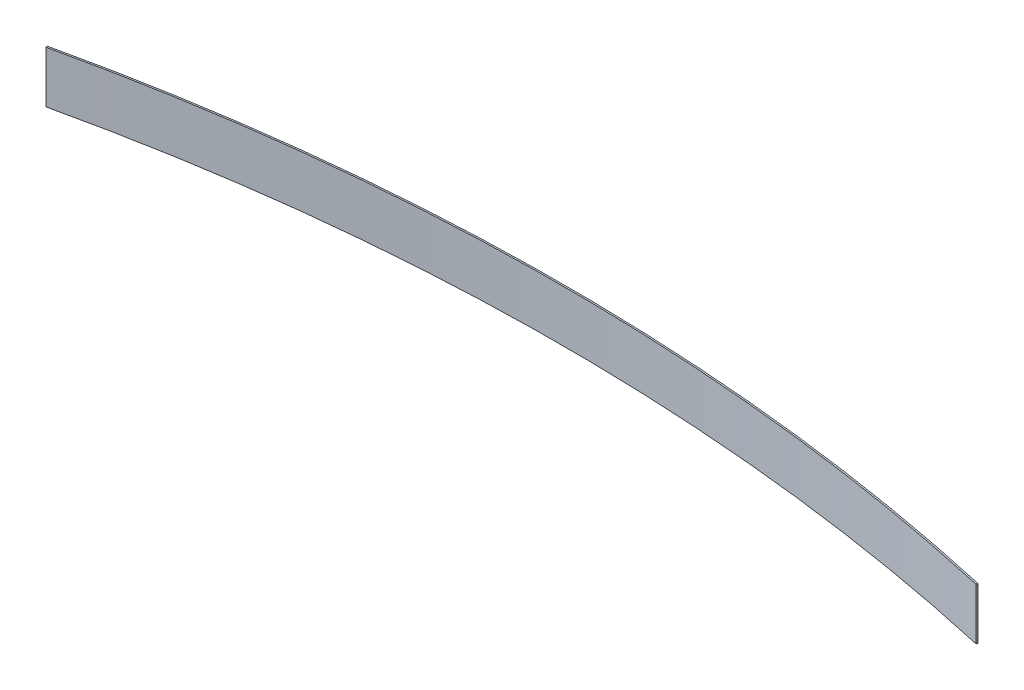
SolidWorks part; units mm, degrees
ref_plane "Front Plane" through (0, 0, 0) normal (0, 0, 1) x (1, 0, 0)
ref_plane "Top Plane" through (0, 0, 0) normal (0, 1, 0) x (1, 0, 0)
ref_plane "Right Plane" through (0, 0, 0) normal (1, 0, 0) x (0, 0, -1)
sketch "Sketch1" plane through (0, 0, 0) normal (0, 1, 0) x (1, 0, 0)
  line L0 (0, 0) -> (1828.8, 0) construction
  line L1 (1828.8, 0) -> (1828.8, 152.4) construction
  line L2 (1828.8, 152.4) -> (0, 152.4) construction
  line L3 (0, 152.4) -> (0, 0) construction
  line L4 (-0.697, 3.0976) -> (0, 0)
  line L5 (1829.497, 3.0976) -> (1828.8, 0)
  line L6 (914.4, 101.6) -> (914.4, 0) construction
  arc A0 (0, 0) -> (1828.8, 0) centre (914.4, -4064) cw
  arc A1 (-0.697, 3.0976) -> (1829.497, 3.0976) centre (914.4, -4064) cw
  dimension "D3" = 101.6
  dimension "D1" = 1828.8
  dimension "D2" = 152.4
  dimension "D4" = 3.175
extrude "Boss-Extrude1" add sketch "Sketch1" along normal blind 101.6
